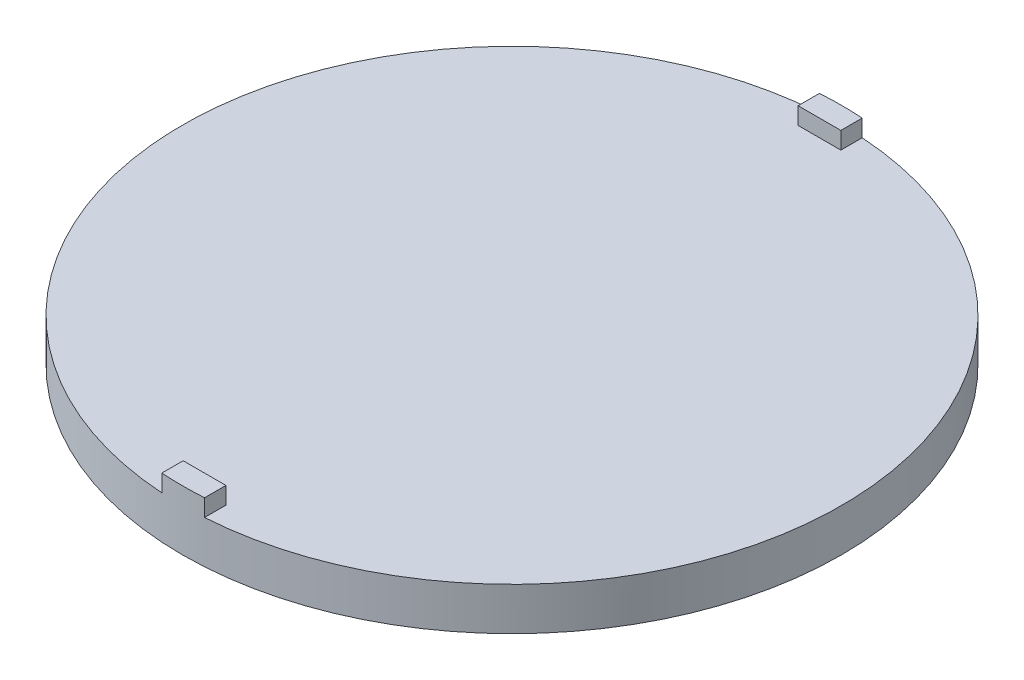
SolidWorks part; units mm, degrees
ref_plane "Front Plane" through (0, 0, 0) normal (0, 0, 1) x (1, 0, 0)
ref_plane "Top Plane" through (0, 0, 0) normal (0, 1, 0) x (1, 0, 0)
ref_plane "Right Plane" through (0, 0, 0) normal (1, 0, 0) x (0, 0, -1)
sketch "Sketch1" plane through (0, 0, 0) normal (0, -1, 0) x (1, 0, 0)
  circle A0 centre (0, 0) radius 24.4774
extrude "Boss-Extrude1" add sketch "Sketch1" along normal blind 3.175
sketch "Sketch2" plane through (0, 0, 0) normal (0, 1, 0) x (1, 0, 0)
  line L0 (1.5875, 24.4259) -> (1.5875, 22.8384) construction
  line L1 (1.5875, 22.8384) -> (-1.5875, 22.8384) construction
  line L2 (-1.5875, 22.8384) -> (-1.5875, 24.4259) construction
  line L3 (-1.5875, -24.4259) -> (-1.5875, -22.8384) construction
  line L4 (-1.5875, -22.8384) -> (1.5875, -22.8384) construction
  line L5 (1.5875, -22.8384) -> (1.5875, -24.4259) construction
  line L6 (1.5875, 24.4259) -> (1.5875, 22.8384)
  line L7 (1.5875, 22.8384) -> (-1.5875, 22.8384)
  line L8 (-1.5875, 22.8384) -> (-1.5875, 24.4259)
  line L9 (-1.5875, -24.4259) -> (-1.5875, -22.8384)
  line L10 (-1.5875, -22.8384) -> (1.5875, -22.8384)
  line L11 (1.5875, -22.8384) -> (1.5875, -24.4259)
  arc A0 (1.5875, 24.4259) -> (-1.5875, 24.4259) centre (0, 0) ccw construction
  arc A1 (-1.5875, -24.4259) -> (1.5875, -24.4259) centre (0, 0) ccw construction
  arc A2 (1.5875, 24.4259) -> (-1.5875, 24.4259) centre (0, 0) ccw
  arc A3 (-1.5875, -24.4259) -> (1.5875, -24.4259) centre (0, 0) ccw
extrude "Boss-Extrude2" add sketch "Sketch2" along normal up to surface (1.27 mm away)
